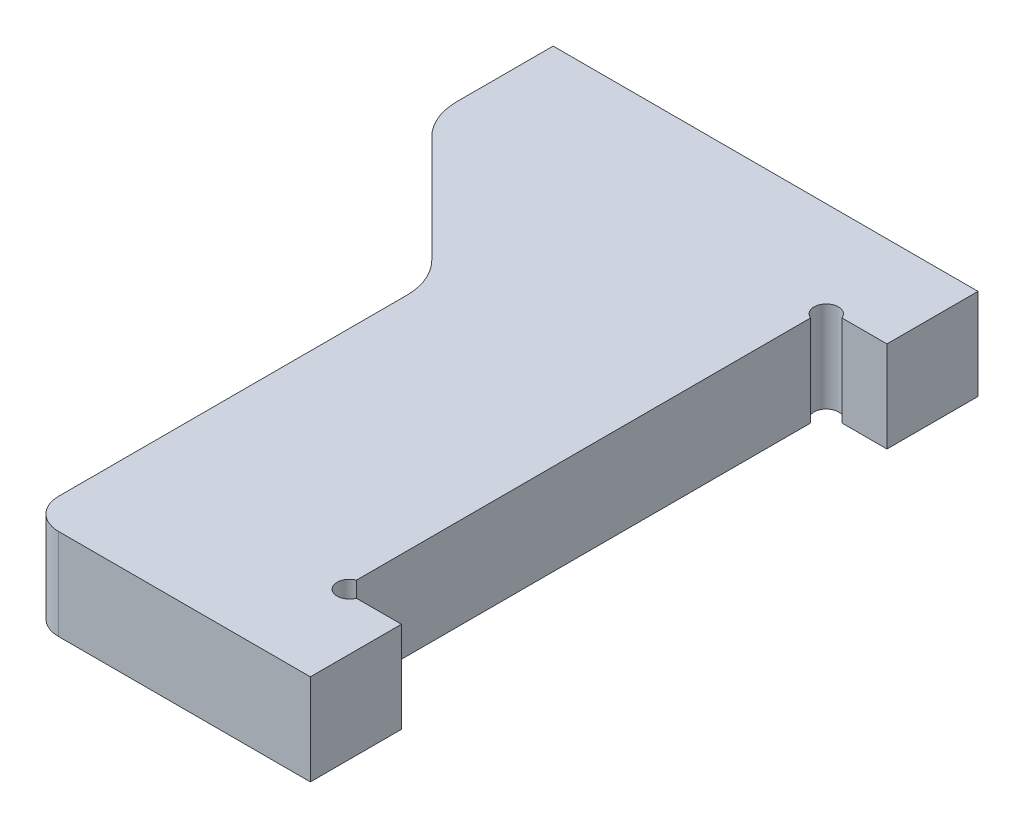
SolidWorks part; units mm, degrees
material "S235JRG2"
ref_plane "Front Plane" through (0, 0, 0) normal (0, 0, 1) x (1, 0, 0)
ref_plane "Top Plane" through (0, 0, 0) normal (0, 1, 0) x (1, 0, 0)
ref_plane "Right Plane" through (0, 0, 0) normal (1, 0, 0) x (0, 0, -1)
sketch "Sketch1" plane through (0, 0, 0) normal (0, 1, 0) x (1, 0, 0)
  line L1 (-18.25, -55) -> (18.25, -55)
  line L2 (-18.25, -55) -> (-18.25, 55)
  line L3 (-18.25, 55) -> (18.25, 55)
  line L4 (18.25, -55) -> (18.25, 55)
  line L5 (-18.25, -55) -> (18.25, 55) construction
  line L6 (-18.25, 55) -> (18.25, -55) construction
  point P0 (0, 0)
  dimension "D1" = 110
  dimension "D2" = 36.5
extrude "Boss-Extrude1" add sketch "Sketch1" along normal blind 15
sketch "Sketch2" plane through (0, 15, 0) normal (0, 1, 0) x (1, 0, 0)
  line L0 (-18.25, 11.5) -> (-41.75, 35)
  line L1 (-18.25, 55) -> (-18.25, -55) construction
  line L2 (-41.75, 35) -> (-41.75, 55)
  line L3 (-41.75, 55) -> (-18.25, 55)
  line L4 (-18.25, 55) -> (-18.25, 11.5)
  line L5 (18.25, -55) -> (18.25, 55) construction
  dimension "D1" = 60
  dimension "D2" = 20
  dimension "D3" = 45
extrude "Boss-Extrude2" add sketch "Sketch2" against normal blind 15
fillet "Fillet1" radius 10 2 edges at (-41.75, 7.5, -35) (-18.25, 7.5, -11.5)
fillet "Fillet2" radius 5 1 edges at (-18.25, 7.5, 55)
sketch "Sketch3" plane through (0, 15, 0) normal (0, 1, 0) x (1, 0, 0)
  line L0 (0, 0) -> (18.25, 0) construction
  line L1 (18.25, -55) -> (28.25, -55)
  line L2 (18.25, -55) -> (18.25, -40)
  line L3 (18.25, -40) -> (28.25, -40)
  line L4 (28.25, -55) -> (28.25, -40)
  line L5 (18.25, -55) -> (18.25, 55) construction
  line L6 (28.25, 55) -> (28.25, 40)
  line L7 (18.25, 40) -> (28.25, 40)
  line L8 (18.25, 55) -> (18.25, 40)
  line L9 (18.25, 55) -> (28.25, 55)
  dimension "D1" = 10
  dimension "D2" = 15
extrude "Boss-Extrude3" add sketch "Sketch3" against normal blind 15
sketch "Sketch4" plane through (0, 15, 0) normal (0, 1, 0) x (1, 0, 0)
  line L0 (18.9571, 39.2929) -> (18.25, 40) construction
  line L1 (18.25, -40) -> (18.25, 40) construction
  line L2 (18.25, 0) -> (51.204, 0) construction
  line L3 (18.9571, -39.2929) -> (18.25, -40) construction
  circle A0 centre (18.9571, 39.2929) radius 2
  circle A1 centre (18.9571, -39.2929) radius 2
  dimension "D2" = 4
  dimension "D1" = 1
  dimension "D3" = 135
extrude "Cut-Extrude1" cut sketch "Sketch4" against normal through all
